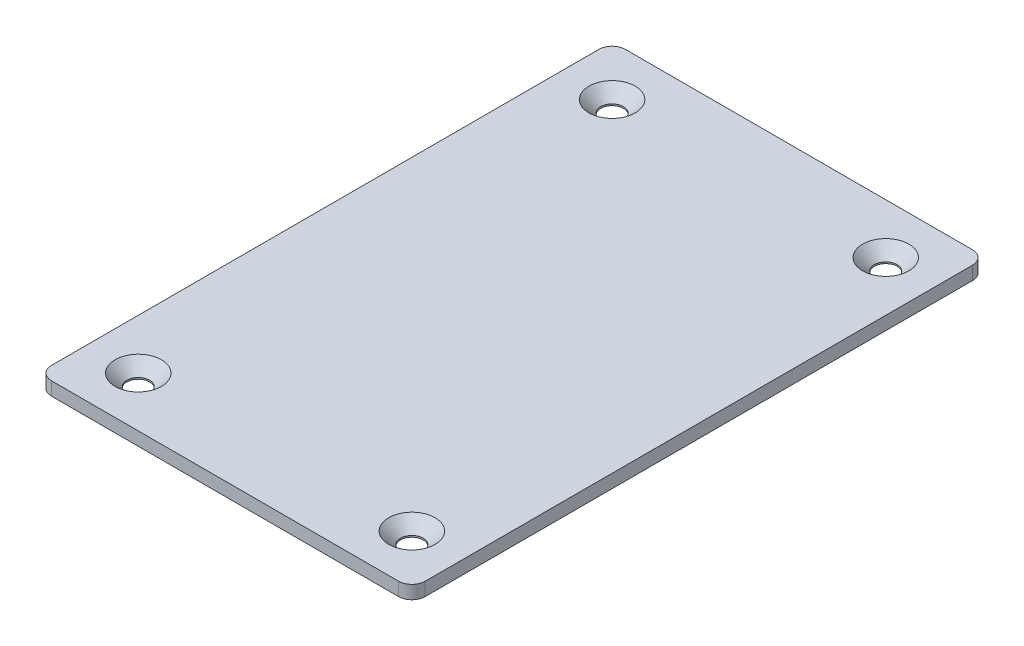
SolidWorks part; units mm, degrees
ref_plane "Ebene vorne" through (0, 0, 0) normal (0, 0, 1) x (1, 0, 0)
ref_plane "Ebene oben" through (0, 0, 0) normal (0, 1, 0) x (1, 0, 0)
ref_plane "Ebene rechts" through (0, 0, 0) normal (1, 0, 0) x (0, 0, -1)
sketch "Skizze1" plane through (0, 0, 0) normal (0, 1, 0) x (1, 0, 0)
  line L1 (0, 0) -> (56, 0)
  line L2 (0, 0) -> (0, 86)
  line L3 (0, 86) -> (56, 86)
  line L4 (56, 0) -> (56, 86)
  dimension "D1" = 56
  dimension "D2" = 86
extrude "Aufsatz-Linear austragen1" add sketch "Skizze1" along normal blind 2
fillet "Verrundung1" radius 2 4 edges at (0, 1, -86) (56, 1, -86) (0, 1, 0) (56, 1, 0)
hole_wizard "Formsenkung für M3 Senkschraube mit Innensechskant1" positions "Skizze2" profile "Skizze3" countersink size "M3" standard "DIN" end condition through all
sketch "Skizze2" plane through (0, 2, 0) normal (0, 1, 0) x (1, 0, 0)
  line L1 (7.5, 7.5) -> (48.5, 7.5) construction
  line L2 (7.5, 7.5) -> (7.5, 78.5) construction
  line L3 (7.5, 78.5) -> (48.5, 78.5) construction
  line L4 (48.5, 7.5) -> (48.5, 78.5) construction
  line L5 (2, 0) -> (54, 0) construction
  line L6 (0, 84) -> (0, 2) construction
  point P0 (7.5, 7.5)
  point P1 (48.5, 78.5)
  point P78 (7.5, 78.5)
  point P79 (48.5, 7.5)
  dimension "D1" = 41
  dimension "D2" = 71
  dimension "D3" = 7.5
  dimension "D4" = 7.5
sketch "Skizze3" plane through (7.5, 2, -7.5) normal (1, 0, 0) x (0, 0, 1)
  line L0 (0, 0) -> (0, 2)
  line L1 (0, 2) -> (1.7, 2)
  line L2 (1.7, 2) -> (1.7, 1.77)
  line L3 (1.7, 1.77) -> (3.47, 0)
  line L5 (3.47, 0) -> (0, 0)
  line L6 (-1.7, 1.77) -> (-3.47, 0) construction
  line L11 (0, -6.35) -> (0, 107.95) construction
  dimension "Bohrerdurchmesser" = 3.4
  dimension "Bohrungstiefe" = 2
  dimension "Senkdurchmesser (Oben)" = 6.94
  dimension "Senkwinkel (Oben)" = 90
